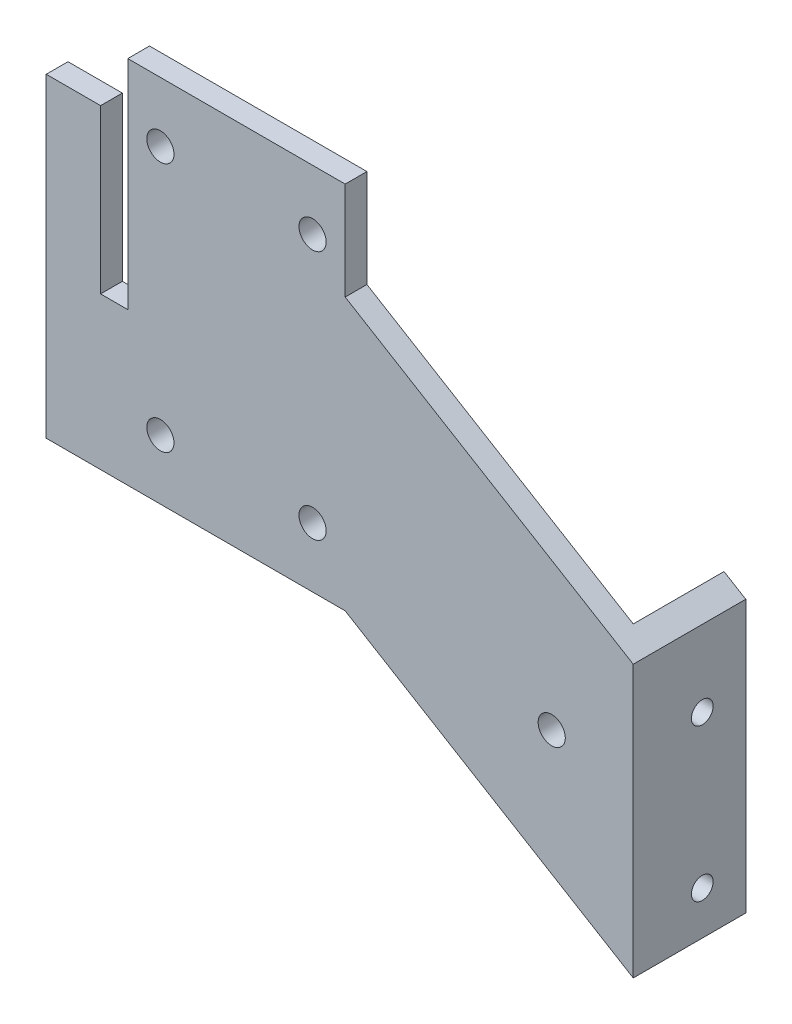
SolidWorks part; units mm, degrees
ref_plane "Спереди" through (0, 0, 0) normal (0, 0, 1) x (1, 0, 0)
ref_plane "Сверху" through (0, 0, 0) normal (0, 1, 0) x (1, 0, 0)
ref_plane "Справа" through (0, 0, 0) normal (1, 0, 0) x (0, 0, -1)
sketch "Эскиз1" plane through (0, 0, 0) normal (0, 0, 1) x (1, 0, 0)
  line L0 (35, 68) -> (35, 0) construction
  line L1 (0, 0) -> (55, 0)
  line L2 (0, 0) -> (0, 68)
  line L3 (0, 68) -> (55, 68)
  line L4 (108, 0) -> (108, 18)
  line L5 (21, 68) -> (21, 0) construction
  line L6 (55, 68) -> (55, 50)
  line L8 (49, 68) -> (49, 0) construction
  line L9 (55, 50) -> (55, 0) construction
  line L10 (108, 0) -> (108, -32)
  line L11 (108, -32) -> (55, 0)
  line L13 (108, 18) -> (55, 50)
  circle A0 centre (21, 57) radius 2.5
  circle A1 centre (49, 57) radius 2.5
  circle A2 centre (21, 11) radius 2.5
  circle A3 centre (49, 11) radius 2.5
  circle A4 centre (93, 0) radius 2.5
  dimension "D8" = 5
  dimension "D9" = 5
  dimension "D10" = 5
  dimension "D11" = 5
  dimension "D18" = 5
  dimension "D1" = 108
  dimension "D2" = 68
  dimension "D3" = 55
  dimension "D4" = 50
  dimension "D5" = 35
  dimension "D6" = 14
  dimension "D7" = 14
  dimension "D12" = 46
  dimension "D13" = 46
  dimension "D14" = 11
  dimension "D15" = 11
  dimension "D16" = 15
  dimension "D17" = 0
  dimension "D19" = 32
extrude "Бобышка-Вытянуть1" add sketch "Эскиз1" along normal blind 4
sketch "Эскиз2" plane through (0, 0, 4) normal (0, 0, 1) x (1, 0, 0)
  line L0 (104, 20.4151) -> (104, -29.5849)
  line L3 (108, 18) -> (108, -32)
  line L6 (108, 18) -> (55, 50) construction
  line L7 (104, 20.4151) -> (108, 18)
  line L8 (108, -32) -> (104, -29.5849)
  line L9 (55, 0) -> (108, -32) construction
  dimension "D1" = 4
extrude "Бобышка-Вытянуть2" add sketch "Эскиз2" against normal blind 20.7
sketch "Эскиз3" plane through (108, 0, 0) normal (1, 0, 0) x (0, 0, -1)
  line L4 (-4, -32) -> (16.7, -32) construction
  line L5 (16.7, -32) -> (16.7, 18) construction
  circle A0 centre (8.7, 4) radius 2
  circle A1 centre (8.7, -24) radius 2
  dimension "D1" = 4
  dimension "D2" = 4
  dimension "D3" = 28
  dimension "D4" = 8
  dimension "D5" = 8
extrude "Вырез-Вытянуть1" cut sketch "Эскиз3" against normal blind 6.7
sketch "Эскиз4" plane through (0, 0, 0) normal (0, 0, -1) x (-1, 0, 0)
  line L1 (0, 68) -> (-15, 68)
  line L2 (0, 68) -> (0, 58)
  line L3 (0, 58) -> (-10, 58)
  line L4 (-15, 68) -> (-15, 48)
  line L6 (-15, 48) -> (-15, 28)
  line L7 (-15, 28) -> (-10, 28)
  line L8 (-10, 58) -> (-10, 28)
  dimension "D1" = 10
  dimension "D2" = 10
  dimension "D3" = 40
  dimension "D4" = 5
extrude "Вырез-Вытянуть3" cut sketch "Эскиз4" against normal blind 10
